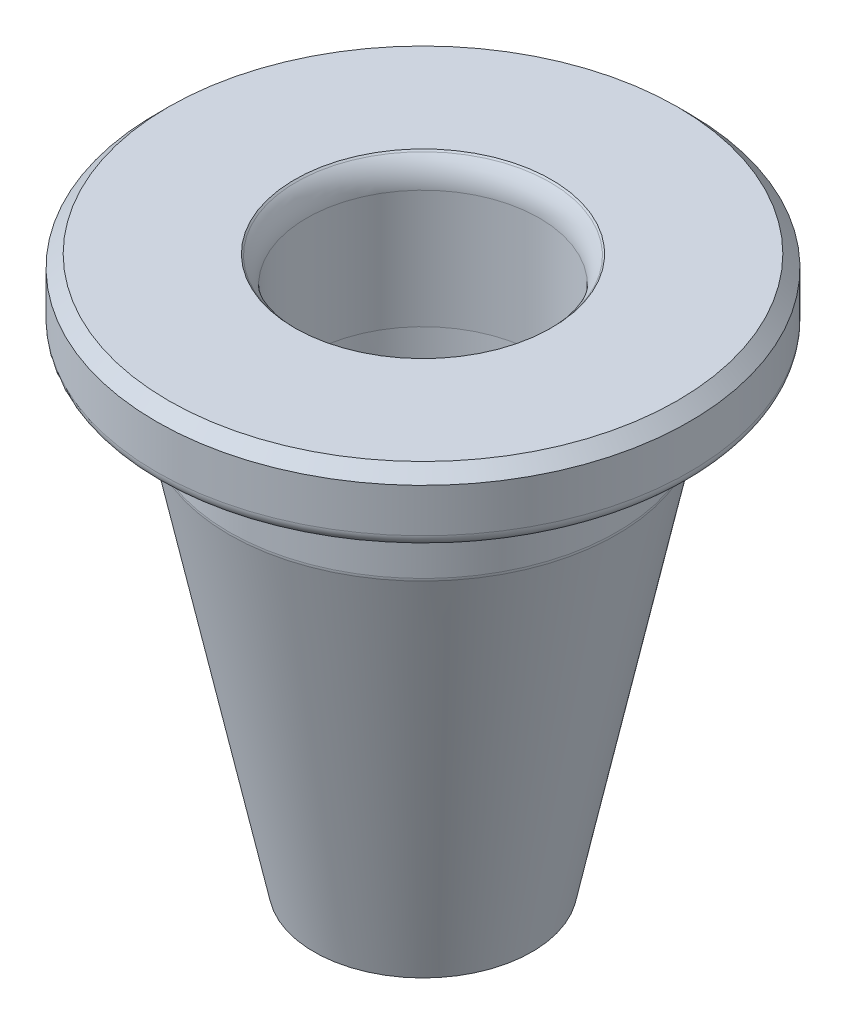
SolidWorks part; units mm, degrees
ref_plane "Ebene vorne" through (0, 0, 0) normal (0, 0, 1) x (1, 0, 0)
ref_plane "Ebene oben" through (0, 0, 0) normal (0, 1, 0) x (1, 0, 0)
ref_plane "Ebene rechts" through (0, 0, 0) normal (1, 0, 0) x (0, 0, -1)
sketch "Skizze1" plane through (0, 0, 0) normal (0, 0, 1) x (1, 0, 0)
  line L0 (0, 0) -> (0, 22) construction
  line L1 (4, 0) -> (4.8, 17)
  line L2 (4.8, 17) -> (4.8, 22)
  line L3 (4.8, 22) -> (8, 22)
  line L5 (8, 22) -> (8, 17)
  line L7 (4, 0) -> (4.5, 0.3)
  line L8 (4.5, 0.3) -> (8, 17)
  dimension "D1" = 9.6
  dimension "D2" = 22
  dimension "D3" = 5
  dimension "D4" = 8
  dimension "D5" = 16
  dimension "D6" = 0.5
  dimension "D7" = 0.3
revolve "Rotation1" add sketch "Skizze1" angle 360 about L0
other "Fläche verschieben2" face at (0, 22, -4.8) parameters "D1"=1
sketch "Skizze2" plane through (0, 23, 0) normal (0, 1, 0) x (1, 0, 0)
  circle A0 centre (0, 0) radius 4.8
  circle A1 centre (0, 0) radius 11
  dimension "D1" = 9.6
  dimension "D2" = 22
extrude "Aufsatz-Linear austragen1" add sketch "Skizze2" against normal blind 2.8
fillet "Verrundung1" radius 0.5 3 edges at (0, 17, -8) (0, 20.2, 11) (0, 20.2, 8)
ref_plane "Ebene1" through (0, 0, 0) normal (0, 0, 1) x (1, 0, 0)
chamfer "Fase1" distance 0.5 angle 45 2 edges at (0, 23, 11) (0, 23, 4.8)
fillet "Verrundung2" radius 1.5 1 edges at (0, 22.5, 4.8)
